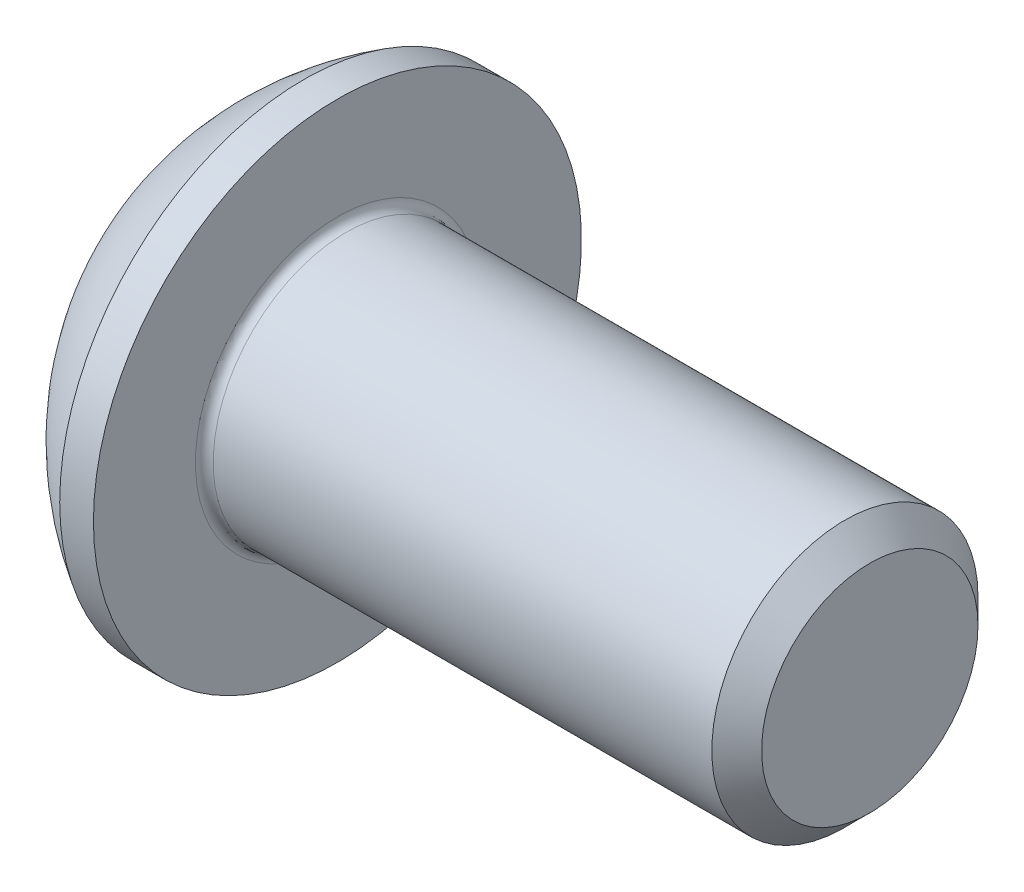
SolidWorks part; units mm, degrees
material "Plain Carbon Steel"
ref_plane "Front Plane" through (0, 0, 0) normal (0, 0, 1) x (1, 0, 0)
ref_plane "Top Plane" through (0, 0, 0) normal (0, 1, 0) x (1, 0, 0)
ref_plane "Right Plane" through (0, 0, 0) normal (1, 0, 0) x (0, 0, -1)
ref_plane "Plane1" through (0, 0, 0) normal (0, 0, -1) x (-1, 0, 0)
sketch "Sketch1" plane through (0, 0, 0) normal (0, 0, -1) x (-1, 0, 0)
  line L0 (-1.65, 2.75) -> (-1.65, 0)
  line L1 (-1.65, 0) -> (0, 0)
  line L2 (0, 0) -> (0, 1.425)
  line L3 (-1.27, 2.75) -> (-1.65, 2.75)
  line L4 (-1.65, 0) -> (0, 0) construction
  arc A0 (0, 1.425) -> (-1.27, 2.75) centre (-2.962, -0.1429) ccw
  dimension "D5" = 3.3514
  dimension "D1" = 2.75
  dimension "D2" = 1.65
  dimension "D3" = 1.425
  dimension "D4" = 0.38
revolve "Revolve1" add sketch "Sketch1" angle 360 about L4
sketch "Sketch2" plane through (0, 0, 0) normal (-1, 0, 0) x (0, 0, 1)
  line L7 (-1, 0.5774) -> (-1, -0.5774)
  line L8 (-1, -0.5774) -> (0, -1.1547)
  line L9 (0, -1.1547) -> (1, -0.5774)
  line L10 (1, -0.5774) -> (1, 0.5774)
  line L11 (1, 0.5774) -> (0, 1.1547)
  line L12 (0, 1.1547) -> (-1, 0.5774)
  circle A0 centre (0, 0) radius 1 construction
  dimension "D1" = 2
extrude "Cut-Extrude1" cut sketch "Sketch2" against normal blind 1.04
sketch "Sketch3" plane through (0, 0, 0) normal (0, 0, 1) x (1, 0, 0)
  line L0 (1.04, 1) -> (1.04, 0)
  line L1 (1.04, 0) -> (1.6174, 0)
  line L2 (1.6174, 0) -> (1.04, 1)
  line L3 (1.04, 0) -> (1.6174, 0) construction
revolve "Cut-Revolve1" cut sketch "Sketch3" angle 360 about L3
sketch "Sketch4" plane through (1.65, 0, 0) normal (1, 0, 0) x (0, 0, -1)
  circle A0 centre (0, 0) radius 1.5
extrude "Largo y Ancho rosca" add sketch "Sketch4" along normal blind 6
fillet "Fillet1" radius 0.1 1 edges at (1.65, 0, -1.5)
chamfer "Chamfer1" distance 0.2805 angle 45 1 edges at (7.65, 0, -1.5)
